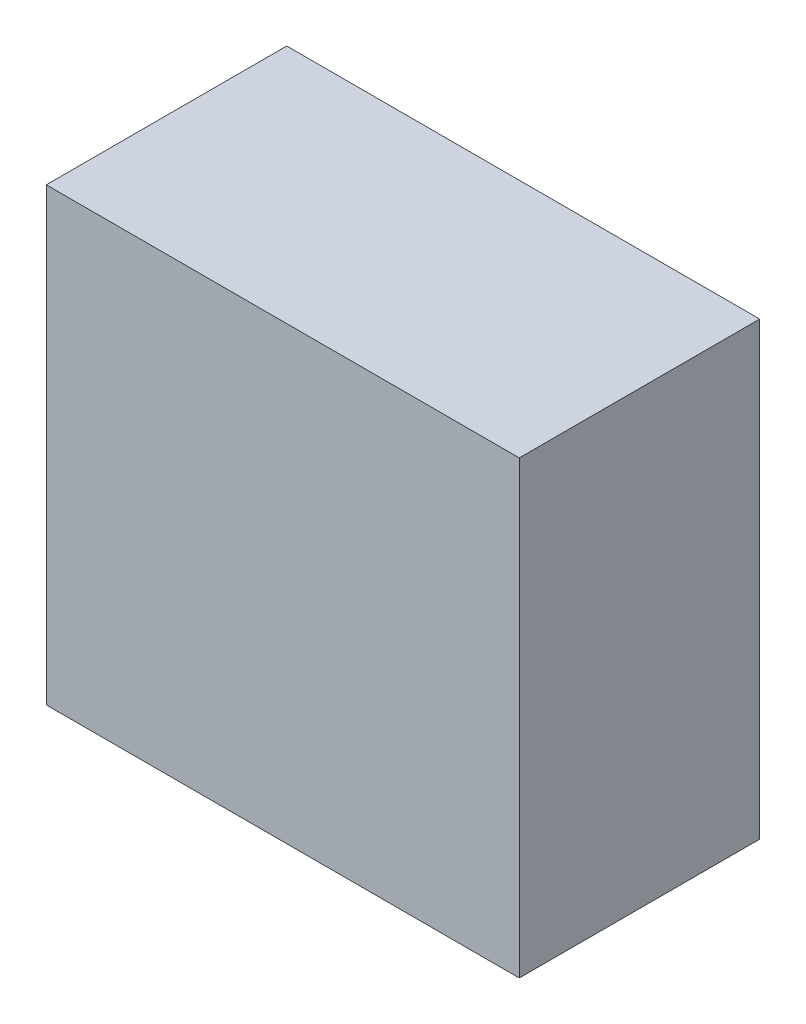
SolidWorks part; units mm, degrees
ref_plane "Front Plane" through (0, 0, 0) normal (0, 0, 1) x (1, 0, 0)
ref_plane "Top Plane" through (0, 0, 0) normal (0, 1, 0) x (1, 0, 0)
ref_plane "Right Plane" through (0, 0, 0) normal (1, 0, 0) x (0, 0, -1)
ref_plane "头部底面" through (0, 15.5, 0) normal (0, 1, 0) x (1, 0, 0)
sketch "头部立方体_草图" plane through (0, 15.5, 0) normal (0, 1, 0) x (1, 0, 0)
  line L1 (-6, 6.35) -> (36, 6.35)
  line L2 (-6, 6.35) -> (-6, -15)
  line L3 (-6, -15) -> (36, -15)
  line L4 (36, 6.35) -> (36, -15)
  dimension "D1" = 42
  dimension "D2" = 21.35
extrude "头部立方体" add sketch "头部立方体_草图" along normal blind 40
sketch "轴体避让槽_草图" plane through (0, 15.5, 0) normal (0, 1, 0) x (1, 0, 0)
  line L1 (6.8, 3.875) -> (23.2, 3.875)
  line L2 (6.8, 3.875) -> (6.8, -12.525)
  line L3 (6.8, -12.525) -> (23.2, -12.525)
  line L4 (23.2, 3.875) -> (23.2, -12.525)
  dimension "D1" = 16.4
  dimension "D2" = 16.4
extrude "轴体避让槽" cut sketch "轴体避让槽_草图" along normal blind 5.6
ref_plane "避让槽顶面" through (0, 21.1, 0) normal (0, 1, 0) x (1, 0, 0)
sketch "十字柱_草图" plane through (0, 21.1, 0) normal (0, 1, 0) x (1, 0, 0)
  circle A0 centre (15, -4.325) radius 2.75
  dimension "D1" = 5.5
extrude "十字柱" add sketch "十字柱_草图" against normal blind 4.3
ref_plane "十字柱底面" through (0, 16.8, 0) normal (0, 1, 0) x (1, 0, 0)
sketch "MX十字插孔_草图" plane through (0, 16.8, 0) normal (0, 1, 0) x (1, 0, 0)
  line L0 (14.325, -2.225) -> (15.675, -2.225)
  line L1 (15.675, -2.225) -> (15.675, -3.65)
  line L2 (15.675, -3.65) -> (17.1, -3.65)
  line L3 (17.1, -3.65) -> (17.1, -5)
  line L4 (17.1, -5) -> (15.675, -5)
  line L5 (15.675, -5) -> (15.675, -6.425)
  line L6 (15.675, -6.425) -> (14.325, -6.425)
  line L7 (14.325, -6.425) -> (14.325, -5)
  line L8 (14.325, -5) -> (12.9, -5)
  line L9 (12.9, -5) -> (12.9, -3.65)
  line L10 (12.9, -3.65) -> (14.325, -3.65)
  line L11 (14.325, -3.65) -> (14.325, -2.225)
extrude "MX十字插孔" cut sketch "MX十字插孔_草图" along normal blind 3.6
ref_plane "刻字面" through (0, 0, -6.35) normal (0, 0, 1) x (1, 0, 0)
sketch "刻字_头部_草图" plane through (0, 0, -6.35) normal (0, 0, 1) x (1, 0, 0)
  line L0 (29.007, 35.514) -> (22.147, 35.514)
  line L1 (22.147, 35.514) -> (22.0688, 36.6449)
  line L2 (22.0688, 36.6449) -> (22.0023, 37.7789)
  line L3 (22.0023, 37.7789) -> (21.9475, 38.916)
  line L4 (21.9475, 38.916) -> (21.9043, 40.0562)
  line L5 (21.9043, 40.0562) -> (21.8728, 41.1996)
  line L6 (21.8728, 41.1996) -> (21.853, 42.346)
  line L7 (21.853, 42.346) -> (19.753, 42.346)
  line L8 (19.753, 42.346) -> (19.795, 40.7329)
  line L9 (19.795, 40.7329) -> (19.837, 39.3096)
  line L10 (19.837, 39.3096) -> (19.879, 38.076)
  line L11 (19.879, 38.076) -> (19.921, 37.0322)
  line L12 (19.921, 37.0322) -> (19.963, 36.1782)
  line L13 (19.963, 36.1782) -> (20.005, 35.514)
  line L14 (20.005, 35.514) -> (15.371, 35.514)
  line L15 (15.371, 35.514) -> (15.371, 33.694)
  line L16 (15.371, 33.694) -> (20.383, 33.694)
  line L17 (20.383, 33.694) -> (20.4133, 33.5941)
  line L18 (20.4133, 33.5941) -> (20.4483, 33.4902)
  line L19 (20.4483, 33.4902) -> (20.488, 33.3825)
  line L20 (20.488, 33.3825) -> (20.5323, 33.2709)
  line L21 (20.5323, 33.2709) -> (20.5813, 33.1554)
  line L22 (20.5813, 33.1554) -> (20.635, 33.036)
  line L23 (20.635, 33.036) -> (19.7977, 32.6506)
  line L24 (19.7977, 32.6506) -> (18.9472, 32.2411)
  line L25 (18.9472, 32.2411) -> (18.0835, 31.8075)
  line L26 (18.0835, 31.8075) -> (17.2066, 31.3498)
  line L27 (17.2066, 31.3498) -> (16.3164, 30.8679)
  line L28 (16.3164, 30.8679) -> (15.413, 30.362)
  line L29 (15.413, 30.362) -> (16.729, 28.612)
  line L30 (16.729, 28.612) -> (17.5219, 29.1195)
  line L31 (17.5219, 29.1195) -> (18.3328, 29.6153)
  line L32 (18.3328, 29.6153) -> (19.1615, 30.0995)
  line L33 (19.1615, 30.0995) -> (20.0081, 30.572)
  line L34 (20.0081, 30.572) -> (20.8726, 31.0328)
  line L35 (20.8726, 31.0328) -> (21.755, 31.482)
  line L36 (21.755, 31.482) -> (22.4542, 30.8781)
  line L37 (22.4542, 30.8781) -> (23.2732, 30.3169)
  line L38 (23.2732, 30.3169) -> (24.212, 29.7985)
  line L39 (24.212, 29.7985) -> (25.2706, 29.3229)
  line L40 (25.2706, 29.3229) -> (26.4489, 28.8901)
  line L41 (26.4489, 28.8901) -> (27.747, 28.5)
  line L42 (27.747, 28.5) -> (27.9741, 28.8348)
  line L43 (27.9741, 28.8348) -> (28.1981, 29.158)
  line L44 (28.1981, 29.158) -> (28.419, 29.4695)
  line L45 (28.419, 29.4695) -> (28.6368, 29.7693)
  line L46 (28.6368, 29.7693) -> (28.8514, 30.0575)
  line L47 (28.8514, 30.0575) -> (29.063, 30.334)
  line L48 (29.063, 30.334) -> (27.3216, 30.7851)
  line L49 (27.3216, 30.7851) -> (25.8492, 31.2798)
  line L50 (25.8492, 31.2798) -> (24.646, 31.818)
  line L51 (24.646, 31.818) -> (23.7119, 32.3998)
  line L52 (23.7119, 32.3998) -> (23.0469, 33.0251)
  line L53 (23.0469, 33.0251) -> (22.651, 33.694)
  line L54 (22.651, 33.694) -> (29.007, 33.694)
  line L55 (29.007, 33.694) -> (29.007, 35.514)
  line L56 (27.467, 39.448) -> (26.8584, 39.1019)
  line L57 (26.8584, 39.1019) -> (26.2459, 38.7449)
  line L58 (26.2459, 38.7449) -> (25.6295, 38.377)
  line L59 (25.6295, 38.377) -> (25.0092, 37.9982)
  line L60 (25.0092, 37.9982) -> (24.3851, 37.6086)
  line L61 (24.3851, 37.6086) -> (23.757, 37.208)
  line L62 (23.757, 37.208) -> (24.947, 35.626)
  line L63 (24.947, 35.626) -> (25.5941, 36.067)
  line L64 (25.5941, 36.067) -> (26.2194, 36.4847)
  line L65 (26.2194, 36.4847) -> (26.823, 36.879)
  line L66 (26.823, 36.879) -> (27.4048, 37.25)
  line L67 (27.4048, 37.25) -> (27.9648, 37.5977)
  line L68 (27.9648, 37.5977) -> (28.503, 37.922)
  line L69 (28.503, 37.922) -> (27.467, 39.448)
  line L70 (26.109, 42.234) -> (25.5257, 41.9373)
  line L71 (25.5257, 41.9373) -> (24.933, 41.6258)
  line L72 (24.933, 41.6258) -> (24.331, 41.2995)
  line L73 (24.331, 41.2995) -> (23.7197, 40.9584)
  line L74 (23.7197, 40.9584) -> (23.099, 40.6026)
  line L75 (23.099, 40.6026) -> (22.469, 40.232)
  line L76 (22.469, 40.232) -> (23.589, 38.664)
  line L77 (23.589, 38.664) -> (24.2237, 39.0778)
  line L78 (24.2237, 39.0778) -> (24.8397, 39.4698)
  line L79 (24.8397, 39.4698) -> (25.437, 39.84)
  line L80 (25.437, 39.84) -> (26.0157, 40.1884)
  line L81 (26.0157, 40.1884) -> (26.5757, 40.5151)
  line L82 (26.5757, 40.5151) -> (27.117, 40.82)
  line L83 (27.117, 40.82) -> (26.109, 42.234)
  line L84 (7.223, 39.35) -> (9.064, 39.35)
  line L85 (9.064, 39.35) -> (7.545, 38.734)
  line L86 (7.545, 38.734) -> (7.6988, 38.4944)
  line L87 (7.6988, 38.4944) -> (7.8569, 38.2518)
  line L88 (7.8569, 38.2518) -> (8.0192, 38.006)
  line L89 (8.0192, 38.006) -> (8.1859, 37.7571)
  line L90 (8.1859, 37.7571) -> (8.3568, 37.5051)
  line L91 (8.3568, 37.5051) -> (8.532, 37.25)
  line L92 (8.532, 37.25) -> (6.915, 37.25)
  line L93 (6.915, 37.25) -> (6.915, 35.682)
  line L94 (6.915, 35.682) -> (14.769, 35.682)
  line L95 (14.769, 35.682) -> (14.769, 37.25)
  line L96 (14.769, 37.25) -> (13.096, 37.25)
  line L97 (13.096, 37.25) -> (13.2346, 37.4616)
  line L98 (13.2346, 37.4616) -> (13.3799, 37.6762)
  line L99 (13.3799, 37.6762) -> (13.5318, 37.894)
  line L100 (13.5318, 37.894) -> (13.6902, 38.1149)
  line L101 (13.6902, 38.1149) -> (13.8553, 38.3389)
  line L102 (13.8553, 38.3389) -> (14.027, 38.566)
  line L103 (14.027, 38.566) -> (12.662, 39.35)
  line L104 (12.662, 39.35) -> (14.447, 39.35)
  line L105 (14.447, 39.35) -> (14.447, 40.918)
  line L106 (14.447, 40.918) -> (11.731, 40.918)
  line L107 (11.731, 40.918) -> (11.8068, 41.1331)
  line L108 (11.8068, 41.1331) -> (11.885, 41.3442)
  line L109 (11.885, 41.3442) -> (11.9655, 41.5515)
  line L110 (11.9655, 41.5515) -> (12.0483, 41.7549)
  line L111 (12.0483, 41.7549) -> (12.1335, 41.9544)
  line L112 (12.1335, 41.9544) -> (12.221, 42.15)
  line L113 (12.221, 42.15) -> (10.121, 42.5)
  line L114 (10.121, 42.5) -> (10.031, 42.2577)
  line L115 (10.031, 42.2577) -> (9.9429, 42.0069)
  line L116 (9.9429, 42.0069) -> (9.8568, 41.7475)
  line L117 (9.8568, 41.7475) -> (9.7726, 41.4796)
  line L118 (9.7726, 41.4796) -> (9.6903, 41.2031)
  line L119 (9.6903, 41.2031) -> (9.61, 40.918)
  line L120 (9.61, 40.918) -> (7.223, 40.918)
  line L121 (7.223, 40.918) -> (7.223, 39.35)
  line L122 (11.213, 37.782) -> (12.172, 37.25)
  line L123 (12.172, 37.25) -> (10.625, 37.25)
  line L124 (10.625, 37.25) -> (10.4004, 37.6019)
  line L125 (10.4004, 37.6019) -> (10.1887, 37.9531)
  line L126 (10.1887, 37.9531) -> (9.9898, 38.3035)
  line L127 (9.9898, 38.3035) -> (9.8037, 38.6531)
  line L128 (9.8037, 38.6531) -> (9.6304, 39.0019)
  line L129 (9.6304, 39.0019) -> (9.47, 39.35)
  line L130 (9.47, 39.35) -> (12.438, 39.35)
  line L131 (12.438, 39.35) -> (12.1765, 39.0459)
  line L132 (12.1765, 39.0459) -> (11.9379, 38.7589)
  line L133 (11.9379, 38.7589) -> (11.7223, 38.489)
  line L134 (11.7223, 38.489) -> (11.5296, 38.2362)
  line L135 (11.5296, 38.2362) -> (11.3598, 38.0006)
  line L136 (11.3598, 38.0006) -> (11.213, 37.782)
  line L137 (2.715, 36.606) -> (2.1717, 36.0052)
  line L138 (2.1717, 36.0052) -> (1.7272, 35.388)
  line L139 (1.7272, 35.388) -> (1.3815, 34.7545)
  line L140 (1.3815, 34.7545) -> (1.1346, 34.1047)
  line L141 (1.1346, 34.1047) -> (0.9864, 33.4385)
  line L142 (0.9864, 33.4385) -> (0.937, 32.756)
  line L143 (0.937, 32.756) -> (0.9542, 32.3851)
  line L144 (0.9542, 32.3851) -> (1.0058, 32.0424)
  line L145 (1.0058, 32.0424) -> (1.0919, 31.7279)
  line L146 (1.0919, 31.7279) -> (1.2123, 31.4416)
  line L147 (1.2123, 31.4416) -> (1.3672, 31.1834)
  line L148 (1.3672, 31.1834) -> (1.5565, 30.9535)
  line L149 (1.5565, 30.9535) -> (1.7997, 30.7564)
  line L150 (1.7997, 30.7564) -> (2.1161, 30.5969)
  line L151 (2.1161, 30.5969) -> (2.5059, 30.4749)
  line L152 (2.5059, 30.4749) -> (2.9689, 30.3904)
  line L153 (2.9689, 30.3904) -> (3.5053, 30.3434)
  line L154 (3.5053, 30.3434) -> (4.115, 30.334)
  line L155 (4.115, 30.334) -> (4.1519, 30.6661)
  line L156 (4.1519, 30.6661) -> (4.1974, 30.9998)
  line L157 (4.1974, 30.9998) -> (4.2515, 31.335)
  line L158 (4.2515, 31.335) -> (4.3141, 31.6718)
  line L159 (4.3141, 31.6718) -> (4.3853, 32.0101)
  line L160 (4.3853, 32.0101) -> (4.465, 32.35)
  line L161 (4.465, 32.35) -> (4.2937, 32.3243)
  line L162 (4.2937, 32.3243) -> (4.1391, 32.3033)
  line L163 (4.1391, 32.3033) -> (4.0013, 32.287)
  line L164 (4.0013, 32.287) -> (3.8801, 32.2753)
  line L165 (3.8801, 32.2753) -> (3.7757, 32.2683)
  line L166 (3.7757, 32.2683) -> (3.688, 32.266)
  line L167 (3.688, 32.266) -> (3.4249, 32.2897)
  line L168 (3.4249, 32.2897) -> (3.2097, 32.3609)
  line L169 (3.2097, 32.3609) -> (3.0422, 32.4795)
  line L170 (3.0422, 32.4795) -> (2.9227, 32.6456)
  line L171 (2.9227, 32.6456) -> (2.8509, 32.8591)
  line L172 (2.8509, 32.8591) -> (2.827, 33.12)
  line L173 (2.827, 33.12) -> (2.8737, 33.6477)
  line L174 (2.8737, 33.6477) -> (3.0137, 34.1856)
  line L175 (3.0137, 34.1856) -> (3.247, 34.7335)
  line L176 (3.247, 34.7335) -> (3.5737, 35.2916)
  line L177 (3.5737, 35.2916) -> (3.9937, 35.8597)
  line L178 (3.9937, 35.8597) -> (4.507, 36.438)
  line L179 (4.507, 36.438) -> (4.2667, 37.019)
  line L180 (4.2667, 37.019) -> (4.031, 37.614)
  line L181 (4.031, 37.614) -> (3.8, 38.223)
  line L182 (3.8, 38.223) -> (3.5737, 38.846)
  line L183 (3.5737, 38.846) -> (3.352, 39.483)
  line L184 (3.352, 39.483) -> (3.135, 40.134)
  line L185 (3.135, 40.134) -> (4.661, 40.134)
  line L186 (4.661, 40.134) -> (4.661, 28.626)
  line L187 (4.661, 28.626) -> (6.453, 28.626)
  line L188 (6.453, 28.626) -> (6.453, 41.758)
  line L189 (6.453, 41.758) -> (1.203, 41.758)
  line L190 (1.203, 41.758) -> (1.203, 40.414)
  line L191 (1.203, 40.414) -> (1.3811, 39.9349)
  line L192 (1.3811, 39.9349) -> (1.5888, 39.3936)
  line L193 (1.5888, 39.3936) -> (1.826, 38.79)
  line L194 (1.826, 38.79) -> (2.0928, 38.1242)
  line L195 (2.0928, 38.1242) -> (2.3891, 37.3962)
  line L196 (2.3891, 37.3962) -> (2.715, 36.606)
  line L197 (14.139, 28.948) -> (14.139, 34.618)
  line L198 (14.139, 34.618) -> (7.545, 34.618)
  line L199 (7.545, 34.618) -> (7.545, 29.032)
  line L200 (7.545, 29.032) -> (9.309, 29.032)
  line L201 (9.309, 29.032) -> (9.309, 29.746)
  line L202 (9.309, 29.746) -> (12.375, 29.746)
  line L203 (12.375, 29.746) -> (12.375, 28.948)
  line L204 (12.375, 28.948) -> (14.139, 28.948)
  line L205 (9.309, 33.05) -> (12.375, 33.05)
  line L206 (12.375, 33.05) -> (12.375, 31.314)
  line L207 (12.375, 31.314) -> (9.309, 31.314)
  line L208 (9.309, 31.314) -> (9.309, 33.05)
extrude "刻字_头部" cut sketch "刻字_头部_草图" along normal blind 0.3
